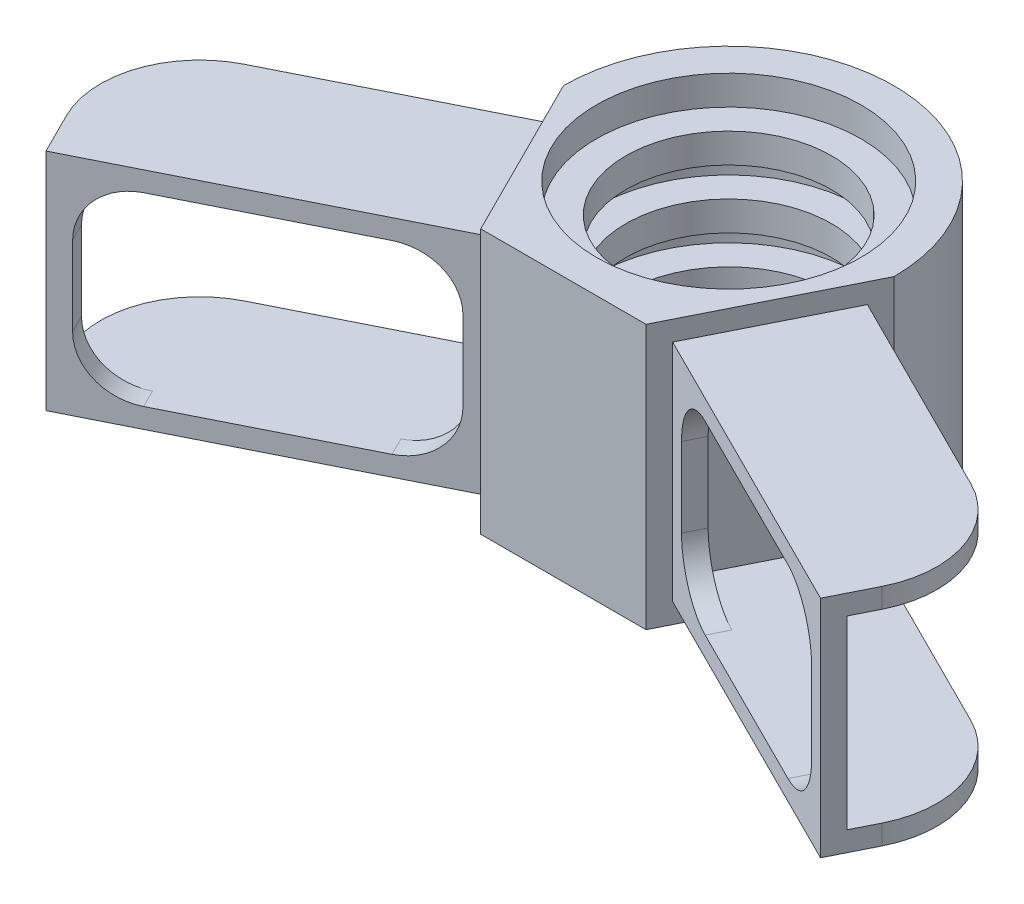
SolidWorks part; units mm, degrees
ref_plane "前视基准面" through (0, 0, 0) normal (0, 0, 1) x (1, 0, 0)
ref_plane "上视基准面" through (0, 0, 0) normal (0, 1, 0) x (1, 0, 0)
ref_plane "右视基准面" through (0, 0, 0) normal (1, 0, 0) x (0, 0, -1)
other "Configuration Table"
sketch "草图1" plane through (0, 0, 0) normal (0, 1, 0) x (1, 0, 0)
  line L0 (-25, 0) -> (-12.5, -25)
  line L1 (-12.5, -25) -> (12.5, -25)
  line L2 (12.5, -25) -> (25, 0)
  line L3 (0, 0) -> (0, -56.7394) construction
  arc A0 (25, 0) -> (-25, 0) centre (0, 0) ccw
  dimension "D1" = 50
  dimension "D2" = 25
  dimension "D3" = 25
extrude "凸台-拉伸1" add sketch "草图1" along normal blind 40
sketch "草图2" plane through (20, 0, 10) normal (0.8944, 0, 0.4472) x (0.4472, 0, -0.8944)
  line L0 (5.1803, 34) -> (-10.7705, 34) construction
  line L1 (-10.7705, 6) -> (5.1803, 6) construction
  line L2 (8.1803, 34) -> (8.1803, 37)
  line L3 (8.1803, 3) -> (8.1803, 37) construction
  line L4 (-10.7705, 6) -> (8.1803, 6)
  line L6 (8.1803, 34) -> (-10.7705, 34)
  line L7 (-10.7705, 34) -> (-10.7705, 6)
  line L8 (-13.7705, 3) -> (8.1803, 3)
  line L9 (8.1803, 3) -> (8.1803, 37)
  line L10 (8.1803, 37) -> (-13.7705, 37)
  line L11 (-13.7705, 37) -> (-13.7705, 3)
  line L12 (-13.7705, 3) -> (8.1803, 3)
  line L13 (8.1803, 3) -> (8.1803, 6)
  line L14 (8.1803, 37) -> (-13.7705, 37)
  line L15 (-13.7705, 37) -> (-13.7705, 3)
  line L16 (5.1803, 6) -> (5.1803, 34) construction
  dimension "D1" = 3
  dimension "D2" = 3
extrude "凸台-拉伸2" add sketch "草图2" along normal blind 50
fillet "圆角1" radius 15 2 edges at (68.3797, 4.5, 25.044) (68.3797, 35.5, 25.044)
sketch "草图3" plane through (-6.1584, 0, 12.3167) normal (-0.4472, 0, 0.8944) x (0.8944, 0, 0.4472)
  line L8 (25.3607, 34) -> (25.3607, 6)
  line L9 (25.3607, 6) -> (69.3607, 6)
  line L10 (69.3607, 6) -> (69.3607, 34)
  line L11 (69.3607, 34) -> (25.3607, 34)
  line L12 (25.3607, 26) -> (25.3607, 14)
  line L13 (33.3607, 6) -> (61.3607, 6)
  line L14 (69.3607, 14) -> (69.3607, 26)
  line L15 (61.3607, 34) -> (33.3607, 34)
  arc A0 (69.3607, 26) -> (61.3607, 34) centre (61.3607, 26) ccw
  arc A1 (61.3607, 6) -> (69.3607, 14) centre (61.3607, 14) ccw
  arc A2 (25.3607, 14) -> (33.3607, 6) centre (33.3607, 14) ccw
  arc A3 (25.3607, 26) -> (33.3607, 34) centre (33.3607, 26) cw
  dimension "D2" = 8
  dimension "D1" = 3
extrude "切除-拉伸1" cut sketch "草图3" against normal blind 50
mirror "镜向2" about plane through (0, 0, 0) normal (1, 0, 0) of "凸台-拉伸2", "圆角1", "切除-拉伸1"
sketch "草图4" plane through (0, 40, 0) normal (0, 1, 0) x (1, 0, 0)
  circle A0 centre (0, 0) radius 20
  arc A1 (25, 0) -> (-25, 0) centre (0, 0) ccw construction
  dimension "D1" = 5
extrude "切除-拉伸2" cut sketch "草图4" against normal blind 4.4444
sketch "草图5" plane through (0, 35.5556, 0) normal (0, 1, 0) x (1, 0, 0)
  circle A0 centre (0, 0) radius 15.5556
  circle A1 centre (0, 0) radius 20 construction
  dimension "D1" = 4.4444
extrude "切除-拉伸3" cut sketch "草图5" against normal through all
pattern_linear "阵列(线性)1" count 5 spacing 8.8889 along (0, -1, 0) of "切除-拉伸2"
equation "\"a\"= 25"
equation "\"b\"= 40"
equation "\"D1@切除-拉伸2\"=\"b\"/9"
equation "\"D1@草图5\"=\"b\"/9"
equation "\"D4@阵列(线性)1\"=\"b\"/4.5"
equation "\"D3@阵列(线性)1\"=\"b\"/4.5"
